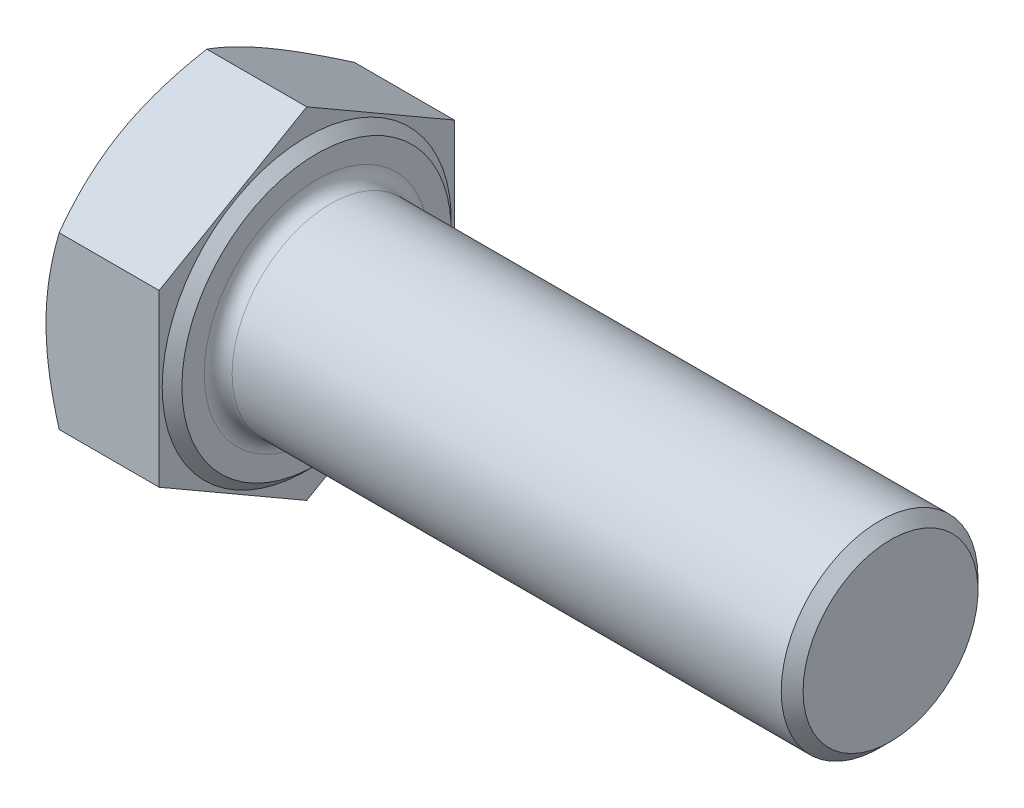
SolidWorks part; units mm, degrees
ref_plane "前视基准面" through (0, 0, 0) normal (0, 0, 1) x (1, 0, 0)
ref_plane "上视基准面" through (0, 0, 0) normal (0, 1, 0) x (1, 0, 0)
ref_plane "右视基准面" through (0, 0, 0) normal (1, 0, 0) x (0, 0, -1)
sketch "草图1" plane through (0, 0, 0) normal (0, 0, 1) x (1, 0, 0)
  line L0 (0, 0) -> (42.5, 0) construction
  line L1 (0, 0) -> (0, 10.015)
  line L2 (0, 10.015) -> (7.5, 10.015)
  line L3 (7.5, 10.015) -> (7.5, 0)
  line L4 (7.5, 6) -> (42.5, 6)
  line L5 (42.5, 6) -> (42.5, 0)
  line L6 (0, 9) -> (0.586, 10.015)
  line L7 (39, 6) -> (39, 0)
  line L8 (12.8, 6) -> (12.8, 0)
  line L9 (7.5, 5.4317) -> (42.5, 5.4317)
  line L10 (42.5, 5.0528) -> (7.5, 5.0528)
  line L11 (6.9, 8.815) -> (7.5, 8.215)
  line L12 (6.9, 10.015) -> (6.9, 0)
  line L13 (7.4, 8.315) -> (7.4, 0) construction
  arc A0 (7.5, 6.85) -> (8.35, 6) centre (8.35, 6.85) ccw
  point P12 (40.75, 0)
  point P13 (2.38, 10.015)
  point P14 (7.5, 6.85)
  point P24 (7.5, 8.315)
  dimension "D1" = 0.1
  dimension "r" = 0.85
  dimension "k" = 7.5
  dimension "D2" = 45
  dimension "β" = 30
  dimension "e" = 20.03
  dimension "s" = 18
  dimension "d" = 12
  dimension "l" = 35
  dimension "D52" = 3.5
  dimension "P" = 1.75
  dimension "kw" = 5.12
  dimension "da" = 13.7
  dimension "a" = 5.3
  dimension "ds" = 10.8634
  dimension "D61" = 10.1056
  dimension "dw" = 16.63
  dimension "c" = 0.6
sketch "草图2" plane through (0, 0, 0) normal (1, 0, 0) x (0, 0, -1)
  line L1 (0, 10.3923) -> (-9, 5.1962)
  line L2 (-9, 5.1962) -> (-9, -5.1962)
  line L3 (-9, -5.1962) -> (0, -10.3923)
  line L4 (0, -10.3923) -> (9, -5.1962)
  line L5 (9, -5.1962) -> (9, 5.1962)
  line L6 (9, 5.1962) -> (0, 10.3923)
  circle A0 centre (0, 0) radius 9 construction
sketch "草图3" plane through (0, 0, 0) normal (1, 0, 0) x (0, 0, -1)
  line L0 (9, 5.1962) -> (0, 10.3923) construction
  line L1 (0, 10.3923) -> (-9, 5.1962) construction
  line L2 (-9, 5.1962) -> (-9, -5.1962) construction
  line L3 (9, -5.1962) -> (9, 5.1962) construction
  line L4 (0, -10.3923) -> (9, -5.1962) construction
  line L5 (-9, -5.1962) -> (0, -10.3923) construction
  line L6 (9, 5.1962) -> (0, 10.3923)
  line L7 (0, 10.3923) -> (-9, 5.1962)
  line L8 (-9, 5.1962) -> (-9, -5.1962)
  line L9 (9, -5.1962) -> (9, 5.1962)
  line L10 (0, -10.3923) -> (9, -5.1962)
  line L11 (-9, -5.1962) -> (0, -10.3923)
extrude "凸台-拉伸1" add sketch "草图3" along normal up to vertex (7.5 mm away) up to point (7.5, 10.015, 0)
sketch "草图4" plane through (0, 0, 0) normal (-1, 0, 0) x (0, 0, 1)
  circle A0 centre (0, 0) radius 9 construction
  circle A1 centre (0, 0) radius 9
  circle A2 centre (0, 0) radius 20.03
  dimension "D1" = 40.06
extrude "切除-拉伸1" cut sketch "草图4" against normal blind 0.9375 draft 60
sketch "草图5" plane through (0, 0, 0) normal (0, 0, 1) x (1, 0, 0)
  line L0 (7.5, 6) -> (42.5, 6) construction
  line L1 (42.5, 6) -> (42.5, 0) construction
  line L2 (0, 0) -> (42.5, 0) construction
  line L3 (8.35, 6) -> (42.5, 6)
  line L4 (42.5, 6) -> (42.5, 0)
  line L5 (7.5, 0) -> (42.5, 0)
  line L6 (7.5, 6.85) -> (7.5, 0)
  arc A0 (7.5, 6.85) -> (8.35, 6) centre (8.35, 6.85) ccw construction
  arc A1 (7.5, 6.85) -> (8.35, 6) centre (8.35, 6.85) ccw
revolve "旋转1" add sketch "草图5" angle 360 about L5
cosmetic thread "装饰螺纹线2" parameters "D1"=29.7, "D2"=10.1056
chamfer "倒角2" distance 0.6667 angle 45 1 edges at (42.5, 0, 6)
sketch "草图7" plane through (0, 0, 0) normal (0, 0, 1) x (1, 0, 0)
  line L0 (7.5, 8.215) -> (6.9, 8.815)
  line L1 (6.9, 8.815) -> (6.9, 20.03)
  line L2 (6.9, 20.03) -> (7.5, 20.03)
  line L3 (7.5, 20.03) -> (7.5, 8.215)
  line L4 (0, 0) -> (42.5, 0) construction
  line L5 (0, 0) -> (42.5, 0) construction
  dimension "D1" = 40.06
revolve "切除-旋转1" cut sketch "草图7" angle 360 mid plane about L5
sketch "草图6" [suppressed] plane through (0, 0, 0) normal (0, 0, 1) x (1, 0, 0)
  line L0 (9.3, 0) -> (9.3, 4) construction
  line L1 (9.3, 4) -> (75.3, 4)
  line L2 (75.3, 4) -> (75.3, 0)
  line L3 (9.3, 4) -> (5.9719, 3.5984)
  line L5 (5.3, 3.5941) -> (75.3, 3.5941) construction
  line L6 (5.3, 7.19) -> (5.3, 0) construction
  line L7 (5.3, 4.1941) -> (5.3, 0)
  line L8 (5.3, 0) -> (75.3, 0)
  arc A0 (5.9719, 3.5984) -> (5.3, 4.1941) centre (5.9, 4.1941) cw
  arc A1 (5.3, 4.6) -> (5.9, 4) centre (5.9, 4.6) ccw construction
revolve "旋转2" [suppressed] add sketch "草图6" angle 360 about L8
cosmetic thread "装饰螺纹线1" [suppressed] parameters "D1"=29.7, "D2"=10.1056
chamfer "倒角1" [suppressed] distance 0.6667 angle 45
sketch "草图8" [suppressed] plane through (0, 0, 0) normal (0, 0, 1) x (1, 0, 0)
  line L0 (5.3, 5.715) -> (4.7, 6.315)
  line L1 (4.7, 6.315) -> (4.7, 14.38)
  line L2 (4.7, 14.38) -> (5.3, 14.38)
  line L3 (5.3, 14.38) -> (5.3, 5.715)
  line L4 (0, 0) -> (75.3, 0) construction
  line L5 (0, 0) -> (75.3, 0) construction
  dimension "D1" = 40.06
revolve "切除-旋转2" [suppressed] cut sketch "草图8" angle 360 mid plane about L5
